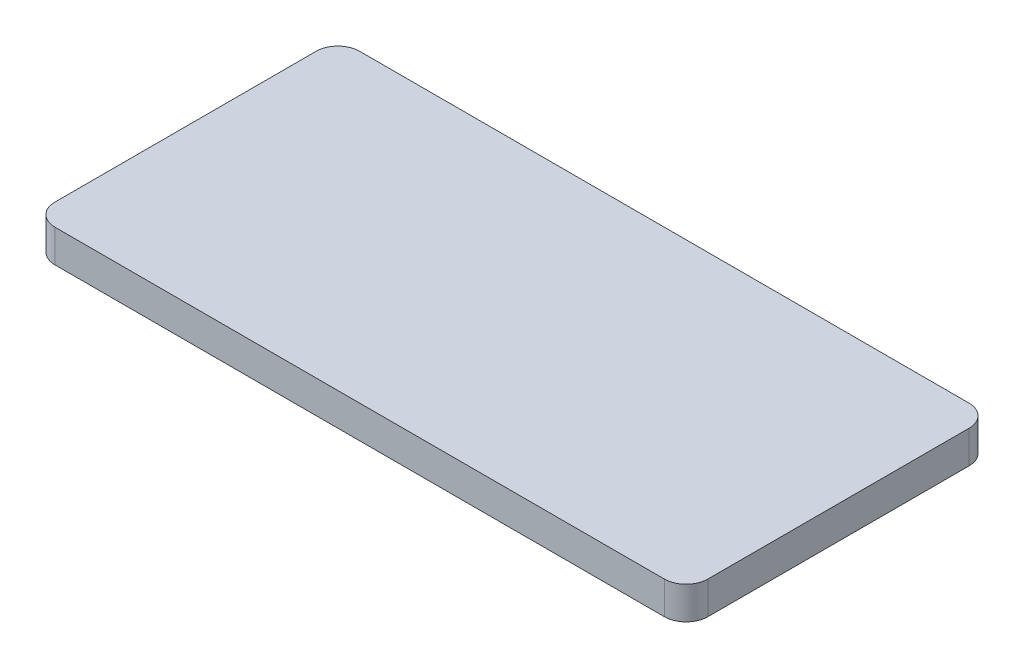
SolidWorks part; units mm, degrees
ref_plane "Front Plane" through (0, 0, 0) normal (0, 0, 1) x (1, 0, 0)
ref_plane "Top Plane" through (0, 0, 0) normal (0, 1, 0) x (1, 0, 0)
ref_plane "Right Plane" through (0, 0, 0) normal (1, 0, 0) x (0, 0, -1)
sketch "Sketch1" plane through (0, 0, 0) normal (0, 1, 0) x (1, 0, 0)
  line L1 (-256.8725, 130.6491) -> (343.1275, 130.6491)
  line L2 (-256.8725, 130.6491) -> (-256.8725, -149.3509)
  line L3 (-256.8725, -149.3509) -> (343.1275, -149.3509)
  line L4 (343.1275, 130.6491) -> (343.1275, -149.3509)
  point P0 (43.1275, -12.7772)
  dimension "D1" = 600
  dimension "D2" = 280
extrude "Boss-Extrude1" add sketch "Sketch1" along normal blind 30
fillet "Fillet1" radius 20 4 edges at (343.1275, 15, 149.3509) (343.1275, 15, -130.6491) (-256.8725, 15, -130.6491) (-256.8725, 15, 149.3509)
